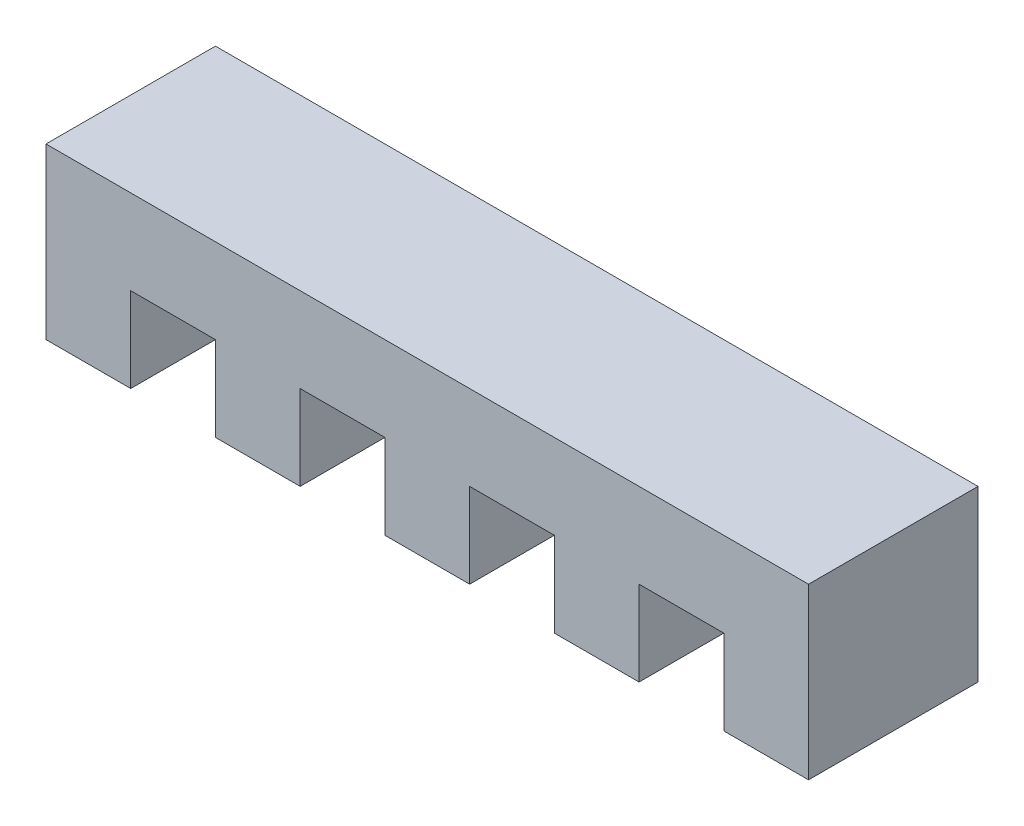
SolidWorks part; units mm, degrees
ref_plane "Plan de face" through (0, 0, 0) normal (0, 0, 1) x (1, 0, 0)
ref_plane "Plan de dessus" through (0, 0, 0) normal (0, 1, 0) x (1, 0, 0)
ref_plane "Plan de droite" through (0, 0, 0) normal (1, 0, 0) x (0, 0, -1)
sketch "Esquisse1" plane through (0, 0, 0) normal (0, 0, 1) x (1, 0, 0)
  line L0 (-5, 0) -> (5, 0)
  line L1 (5, 0) -> (5, 10)
  line L2 (5, 10) -> (15, 10)
  line L3 (15, 10) -> (15, 0)
  line L4 (15, 0) -> (25, 0)
  line L5 (25, 0) -> (25, 10)
  line L6 (25, 10) -> (35, 10)
  line L7 (35, 10) -> (35, 0)
  line L8 (35, 0) -> (45, 0)
  line L9 (45, 0) -> (45, 20)
  line L10 (45, 20) -> (-45, 20)
  line L11 (-45, 20) -> (-45, 0)
  line L12 (-45, 0) -> (-35, 0)
  line L13 (-35, 0) -> (-35, 10)
  line L14 (-35, 10) -> (-25, 10)
  line L15 (-25, 10) -> (-25, 0)
  line L16 (-25, 0) -> (-15, 0)
  line L17 (-15, 0) -> (-15, 10)
  line L18 (-15, 10) -> (-5, 10)
  line L19 (-5, 10) -> (-5, 0)
  point P20 (0, 0)
  dimension "D1" = 10
  dimension "D2" = 90
  dimension "D3" = 10
  dimension "D4" = 20
extrude "Boss.-Extru.1" add sketch "Esquisse1" along normal blind 20
sketch "Esquisse2" plane through (0, 20, 0) normal (0, 1, 0) x (1, 0, 0)
  line L0 (0, 0) -> (0, -20) construction
  line L1 (45, 0) -> (-45, 0) construction
  line L2 (45, -20) -> (-45, -20) construction
sketch "Esquisse3" plane through (0, 0, 20) normal (0, 0, 1) x (1, 0, 0)
  line L0 (0, 20) -> (0, 0) construction
  line L1 (-5, 0) -> (5, 0) construction
